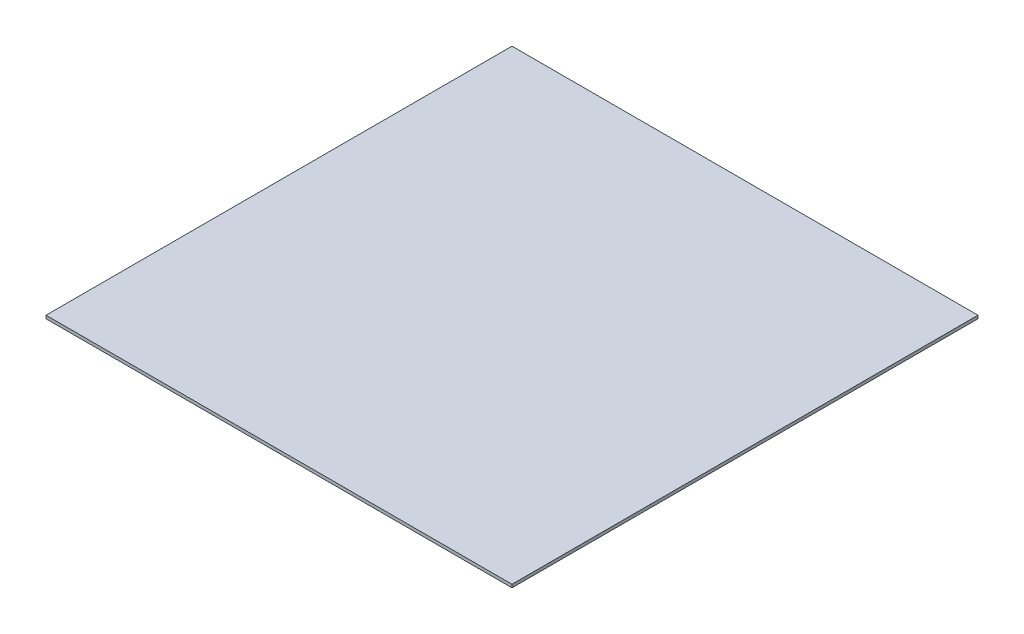
SolidWorks part; units mm, degrees
material "1023 Carbon Steel Sheet (SS)"
ref_plane "Front Plane" through (0, 0, 0) normal (0, 0, 1) x (1, 0, 0)
ref_plane "Top Plane" through (0, 0, 0) normal (0, 1, 0) x (1, 0, 0)
ref_plane "Right Plane" through (0, 0, 0) normal (1, 0, 0) x (0, 0, -1)
sketch "Sketch1" plane through (0, 0, 0) normal (0, 1, 0) x (1, 0, 0)
  line L1 (0, 0) -> (300, 0)
  line L2 (0, 0) -> (0, 300)
  line L3 (0, 300) -> (300, 300)
  line L4 (300, 0) -> (300, 300)
extrude "Boss-Extrude1" add sketch "Sketch1" along normal blind 2
